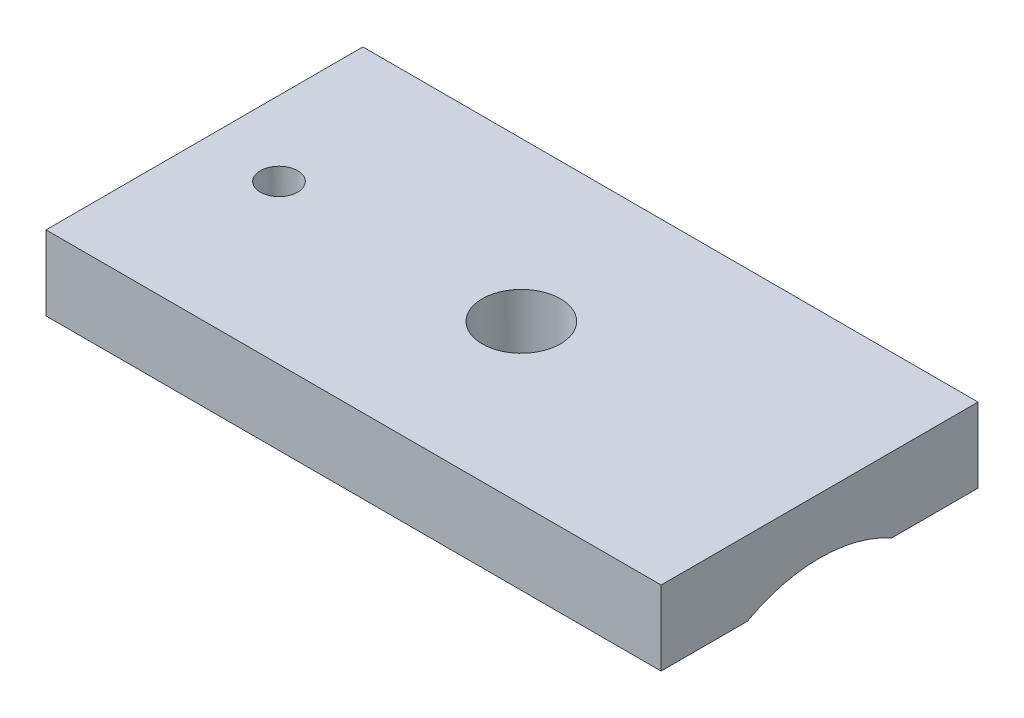
SolidWorks part; units mm, degrees
material "Brass"
ref_plane "Front Plane" through (0, 0, 0) normal (0, 0, 1) x (1, 0, 0)
ref_plane "Top Plane" through (0, 0, 0) normal (0, 1, 0) x (1, 0, 0)
ref_plane "Right Plane" through (0, 0, 0) normal (1, 0, 0) x (0, 0, -1)
sketch "Sketch2" plane through (0, 0, 0) normal (0, 1, 0) x (1, 0, 0)
  line L1 (16.5, -8.5) -> (-16.5, -8.5)
  line L2 (16.5, -8.5) -> (16.5, 8.5)
  line L3 (16.5, 8.5) -> (-16.5, 8.5)
  line L4 (-16.5, -8.5) -> (-16.5, 8.5)
  line L5 (16.5, -8.5) -> (-16.5, 8.5) construction
  line L6 (16.5, 8.5) -> (-16.5, -8.5) construction
  point P0 (0, 0)
  dimension "D1" = 33
  dimension "D2" = 17
extrude "Boss-Extrude1" add sketch "Sketch2" along normal mid plane 4
sketch "Sketch3" plane through (0, 2, 0) normal (0, 1, 0) x (1, 0, 0)
  line L0 (16.5, 0) -> (0.5, 0)
  line L1 (16.5, -8.5) -> (16.5, 8.5) construction
  line L2 (0.5, 0) -> (-12.5, 0)
  dimension "D1" = 16
  dimension "D2" = 29
hole_wizard "M5 Tapped Hole1" positions "3DSketch1" profile "Sketch4" tap size "M5" standard "ISO" end condition through all
sketch3d "3DSketch1"
  point P0 (0.5, 2, 0)
sketch "Sketch4" plane through (0.5, 2, 0) normal (1, 0, 0) x (0, 0, 1)
  line L0 (0, 0) -> (0, 4)
  line L1 (0, 4) -> (2.1, 4)
  line L2 (2.1, 4) -> (2.1, 0)
  line L5 (2.1, 0) -> (0, 0)
  line L11 (0, -6.35) -> (0, 107.95) construction
  dimension "Thru Tap Drill Dia." = 4.2
  dimension "Thru Tap Drill Depth" = 4
cosmetic thread "Hole Thread1" parameters "D2"=5
hole_wizard "Ø2.0mm Dowel Hole1" positions "3DSketch2" profile "Sketch5" hole size "Ø2.0" standard "ISO" end condition through all
sketch3d "3DSketch2"
  point P0 (-12.5, 2, 0)
sketch "Sketch5" plane through (-12.5, 2, 0) normal (1, 0, 0) x (0, 0, 1)
  line L0 (0, 0) -> (0, 4)
  line L1 (0, 4) -> (1, 4)
  line L2 (1, 4) -> (1, 0)
  line L5 (1, 0) -> (0, 0)
  line L11 (0, -6.35) -> (0, 107.95) construction
  dimension "Thru Hole Dia." = 2
  dimension "Thru Hole Depth" = 4
sketch "Sketch6" plane through (16.5, 0, 0) normal (1, 0, 0) x (0, 0, -1)
  line L0 (0, 10.2492) -> (0, -10.2492) construction
  line L4 (-8.5, -2) -> (8.5, -2) construction
  circle A0 centre (0, -9) radius 8
  dimension "D1" = 16
  dimension "D2" = 1
extrude "Cut-Extrude1" cut sketch "Sketch6" against normal through all
